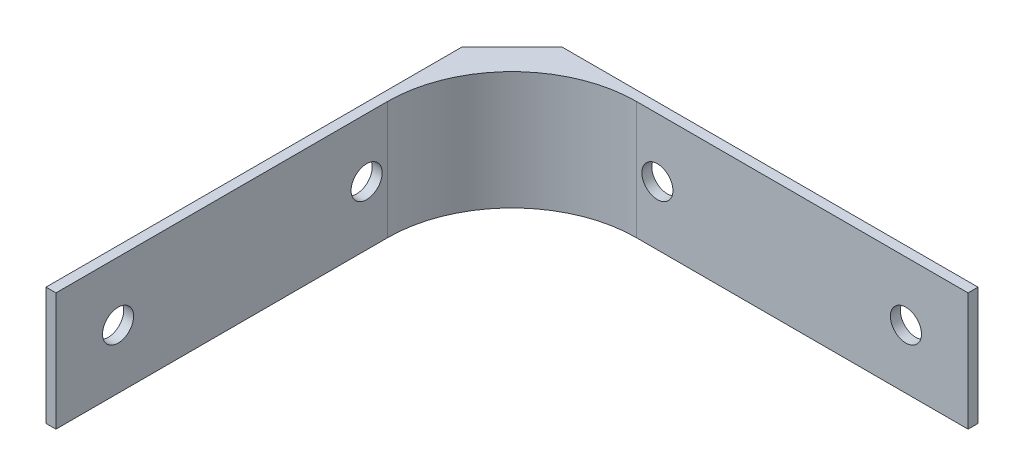
SolidWorks part; units mm, degrees
ref_plane "前视基准面" through (0, 0, 0) normal (0, 0, 1) x (1, 0, 0)
ref_plane "上视基准面" through (0, 0, 0) normal (0, 1, 0) x (1, 0, 0)
ref_plane "右视基准面" through (0, 0, 0) normal (1, 0, 0) x (0, 0, -1)
other "Configuration Table"
sketch "草图1" plane through (0, 0, 0) normal (0, 1, 0) x (1, 0, 0)
  line L0 (8, 0) -> (0, -8)
  line L1 (0, 0) -> (75, 0)
  line L3 (21.6, -1.6) -> (75, -1.6)
  line L4 (75, 0) -> (75, -1.6)
  line L6 (0, 0) -> (0, -75)
  line L7 (0, -75) -> (1.6, -75)
  line L8 (1.6, -21.6) -> (1.6, -75)
  arc A0 (21.6, -1.6) -> (1.6, -21.6) centre (21.6, -21.6) ccw
  point P11 (1.6, -1.6)
  dimension "D5" = 20
  dimension "D1" = 75
  dimension "D2" = 1.6
  dimension "D3" = 1.6
  dimension "D4" = 73.4
  dimension "D6" = 67
  dimension "D7" = 67
extrude "凸台-拉伸2" add sketch "草图1" along normal blind 19 contours A0 L3 L4 L1 L0 L6 L7 L8
sketch "草图2" plane through (0, 0, 1.6) normal (0, 0, 1) x (1, 0, 0)
  line L0 (21.6, 9.5) -> (75, 9.5) construction
  line L1 (21.6, 19) -> (21.6, 0) construction
  line L2 (75, 19) -> (75, 0) construction
  circle A0 centre (25, 9.5) radius 2.5
  circle A1 centre (65, 9.5) radius 2.5
  dimension "D1" = 5
  dimension "D2" = 5
  dimension "D3" = 40
  dimension "D4" = 10
extrude "切除-拉伸1" cut sketch "草图2" against normal through all
sketch "草图3" plane through (1.6, 0, 0) normal (1, 0, 0) x (0, 0, -1)
  line L0 (-75, 9.5) -> (-21.6, 9.5) construction
  line L1 (-75, 19) -> (-75, 0) construction
  line L2 (-21.6, 19) -> (-21.6, 0) construction
  circle A0 centre (-65, 9.5) radius 2.5
  circle A1 centre (-25, 9.5) radius 2.5
  point P10 (0, 0)
  point P12 (-71.9404, 11.3997)
  point P13 (-68.2226, 9.5)
  dimension "D1" = 5
  dimension "D2" = 5
  dimension "D3" = 40
  dimension "D4" = 10
extrude "切除-拉伸2" cut sketch "草图3" against normal through all
